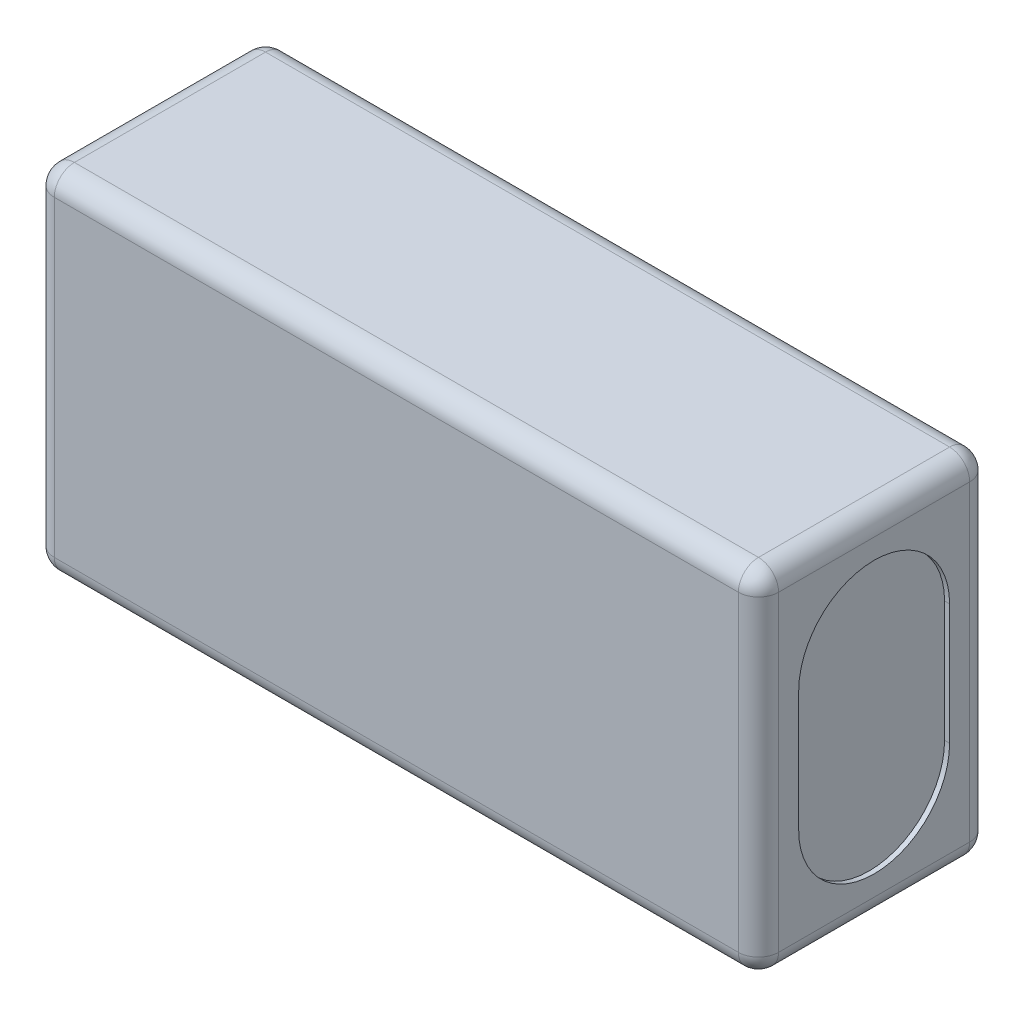
SolidWorks part; units mm, degrees
ref_plane "Plano frontal" through (0, 0, 0) normal (0, 0, 1) x (1, 0, 0)
ref_plane "Plano superior" through (0, 0, 0) normal (0, 1, 0) x (1, 0, 0)
ref_plane "Plano direito" through (0, 0, 0) normal (1, 0, 0) x (0, 0, -1)
sketch "Esboço1" plane through (0, 0, 0) normal (0, 0, 1) x (1, 0, 0)
  line L1 (-36, 17.5) -> (36, 17.5)
  line L2 (-36, 17.5) -> (-36, -17.5)
  line L3 (-36, -17.5) -> (36, -17.5)
  line L4 (36, 17.5) -> (36, -17.5)
  line L5 (-36, 17.5) -> (36, -17.5) construction
  line L6 (-36, -17.5) -> (36, 17.5) construction
  point P0 (0, 0)
  dimension "D1" = 72
  dimension "D2" = 35
extrude "Ressalto-extrusão1" add sketch "Esboço1" along normal blind 23
sketch "Esboço2" plane through (36, 0, 0) normal (1, 0, 0) x (0, 0, -1)
  line L0 (-11.5, 17.5) -> (-11.5, -17.5) construction
  line L1 (-23, 17.5) -> (0, 17.5) construction
  line L2 (-23, -17.5) -> (0, -17.5) construction
  line L3 (0, 0) -> (-23, 0) construction
  line L4 (-23, -17.5) -> (-23, 17.5) construction
  line L5 (-11.5, 6) -> (-11.5, -6) construction
  line L6 (-4, 6) -> (-4, -6)
  line L7 (-19, 6) -> (-19, -6)
  arc A0 (-4, 6) -> (-19, 6) centre (-11.5, 6) ccw
  arc A1 (-19, -6) -> (-4, -6) centre (-11.5, -6) ccw
  point P13 (-11.5, 0)
  dimension "D1" = 12
  dimension "D2" = 15
extrude "Corte-extrusão1" cut sketch "Esboço2" against normal blind 0.5
mirror "Espelhar1" about plane through (0, 0, 0) normal (1, 0, 0) of "Corte-extrusão1"
fillet "Filete1" radius 2 12 edges at (-36, -17.5, 11.5) (36, -17.5, 11.5) (-36, 0, 0) (0, -17.5, 0) (36, 0, 0) (36, 17.5, 11.5) (-36, 17.5, 11.5) (0, 17.5, 0) (0, -17.5, 23) (-36, 0, 23) (0, 17.5, 23) (36, 0, 23)
